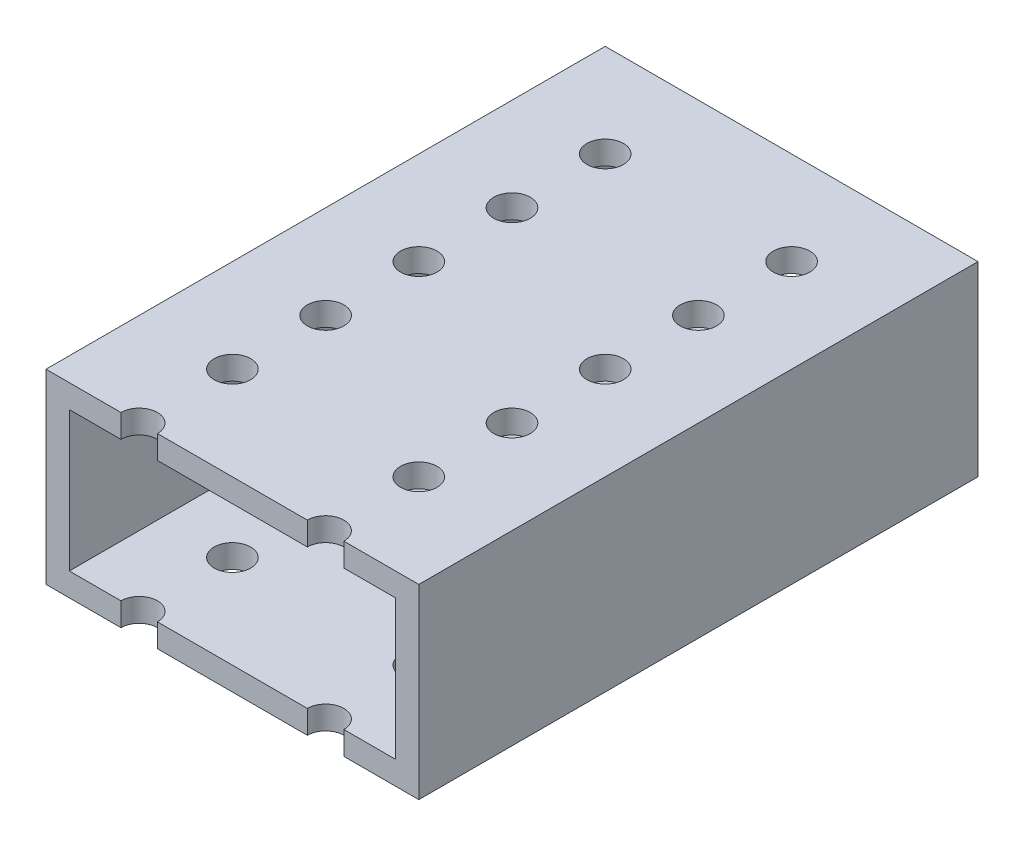
SolidWorks part; units mm, degrees
ref_plane "Front Plane" through (0, 0, 0) normal (0, 0, 1) x (1, 0, 0)
ref_plane "Top Plane" through (0, 0, 0) normal (0, 1, 0) x (1, 0, 0)
ref_plane "Right Plane" through (0, 0, 0) normal (1, 0, 0) x (0, 0, -1)
sketch "Sketch1" plane through (0, 0, 0) normal (0, 0, 1) x (1, 0, 0)
  line L1 (-25.4, -12.7) -> (25.4, -12.7)
  line L2 (-25.4, -12.7) -> (-25.4, 12.7)
  line L3 (-25.4, 12.7) -> (25.4, 12.7)
  line L4 (25.4, -12.7) -> (25.4, 12.7)
  line L5 (-25.4, -12.7) -> (25.4, 12.7) construction
  line L6 (-25.4, 12.7) -> (25.4, -12.7) construction
  point P0 (0, 0)
  dimension "D1" = 50.8
  dimension "D2" = 25.4
extrude "Boss-Extrude1" add sketch "Sketch1" along normal mid plane 76.2
shell "Shell1" thickness 3.175
sketch "Sketch2" plane through (0, 0, 0) normal (0, 1, 0) x (1, 0, 0)
  line L0 (25.4, 38.1) -> (-25.4, 38.1) construction
  line L1 (-25.4, -38.1) -> (-25.4, 38.1) construction
  circle A0 centre (-12.7, 25.4) radius 2.4892
  circle A1 centre (12.7, 25.4) radius 2.4892
  circle A2 centre (12.7, 12.7) radius 2.4892
  circle A3 centre (12.7, 0) radius 2.4892
  circle A4 centre (12.7, -12.7) radius 2.4892
  circle A5 centre (12.7, -25.4) radius 2.4892
  circle A6 centre (12.7, -38.1) radius 2.4892
  circle A7 centre (-12.7, 12.7) radius 2.4892
  circle A8 centre (-12.7, 0) radius 2.4892
  circle A9 centre (-12.7, -12.7) radius 2.4892
  circle A10 centre (-12.7, -25.4) radius 2.4892
  circle A11 centre (-12.7, -38.1) radius 2.4892
  dimension "D1" = 4.9784
  dimension "D7" = 12.7
  dimension "D2" = 12.7
  dimension "D3" = 12.7
  dimension "D6" = 25.4
  dimension "D4" = 2
  dimension "D5" = 6
extrude "Cut-Extrude1" cut sketch "Sketch2" against normal mid plane 127
